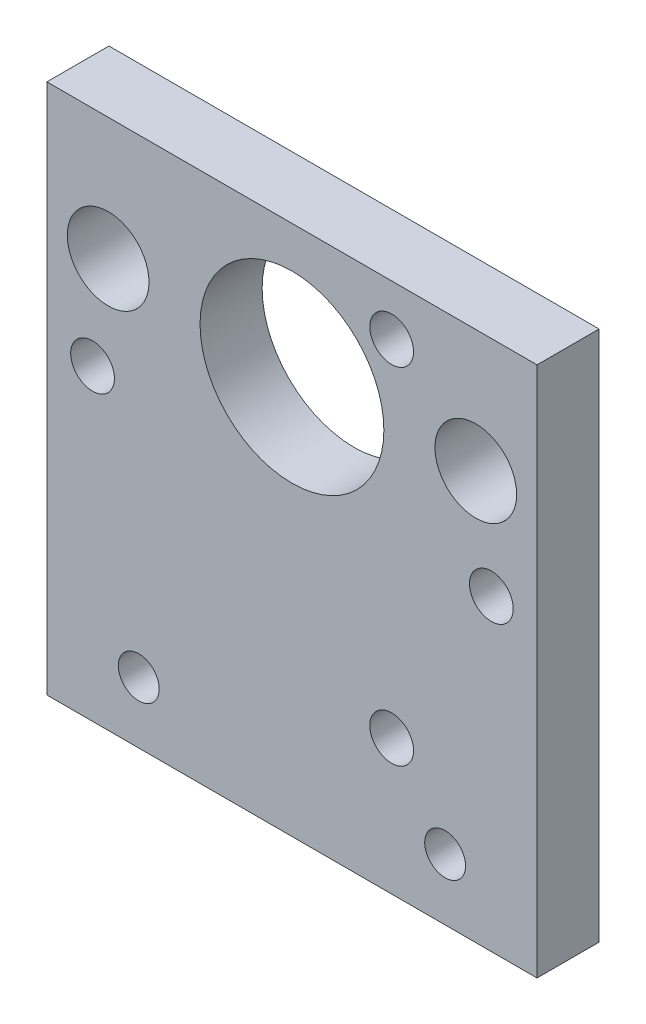
SolidWorks part; units mm, degrees
material "6063-O"
ref_plane "Front" through (0, 0, 0) normal (0, 0, 1) x (1, 0, 0)
ref_plane "Top" through (0, 0, 0) normal (0, 1, 0) x (1, 0, 0)
ref_plane "Right" through (0, 0, 0) normal (1, 0, 0) x (0, 0, -1)
sketch "Sketch1" plane through (0, 0, 0) normal (0, 0, 1) x (1, 0, 0)
  line L1 (19.05, -20.6375) -> (-19.05, -20.6375)
  line L2 (19.05, -20.6375) -> (19.05, 20.6375)
  line L3 (19.05, 20.6375) -> (-19.05, 20.6375)
  line L4 (-19.05, -20.6375) -> (-19.05, 20.6375)
  line L5 (19.05, -20.6375) -> (-19.05, 20.6375) construction
  line L6 (19.05, 20.6375) -> (-19.05, -20.6375) construction
  point P0 (0, 0)
  dimension "D1" = 38.1
  dimension "D2" = 41.275
extrude "Boss-Extrude1" add sketch "Sketch1" along normal blind 4.826
sketch "Sketch2" plane through (0, 0, 4.826) normal (0, 0, 1) x (1, 0, 0)
  line L0 (19.05, 20.6375) -> (-19.05, 20.6375) construction
  line L1 (0, 0) -> (0, 18.787) construction
  line L2 (-15.5, 3.287) -> (15.5, 3.287) construction
  line L3 (7.75, -10.1364) -> (0, 3.287) construction
  line L4 (0, 3.287) -> (7.75, 16.7104) construction
  line L5 (-14.2875, 11.1125) -> (14.2875, 11.1125) construction
  line L6 (-19.05, 20.6375) -> (-19.05, -20.6375) construction
  circle A0 centre (0, 10.287) radius 7.1438
  circle A1 centre (0, 3.287) radius 15.5 construction
  circle A4 centre (7.75, 16.7104) radius 1.7
  circle A5 centre (7.75, -10.1364) radius 1.7
  circle A6 centre (-15.5, 3.287) radius 1.7
  circle A7 centre (15.5, 3.287) radius 1.7
  circle A8 centre (-14.2875, 11.1125) radius 3.175
  circle A9 centre (14.2875, 11.1125) radius 3.175
  point P23 (0, 11.1125)
  dimension "D2" = 14.2875
  dimension "D3" = 31
  dimension "D5" = 3.4
  dimension "D10" = 6.35
  dimension "D1" = 10.3505
  dimension "D4" = 7
  dimension "D6" = 120
  dimension "D7" = 30
  dimension "D8" = 9.525
  dimension "D9" = 4.7625
extrude "Cut-Extrude1" cut sketch "Sketch2" against normal through all contours A0
hole_wizard "Ø3.4 (3.4) Diameter Hole1" positions "Sketch3" profile "Sketch4" hole size "Ø3.4" standard "ANSI Metric" end condition through all
sketch "Sketch3" plane through (0, 0, 4.826) normal (0, 0, 1) x (1, 0, 0)
  point P0 (-15.5, 3.287)
  point P3 (7.75, 16.7104)
  point P6 (15.5, 3.287)
  point P9 (7.75, -10.1364)
sketch "Sketch4" plane through (-15.5, 3.287, 4.826) normal (1, 0, 0) x (0, -1, 0)
  line L0 (0, 0) -> (0, 4.826)
  line L1 (0, 4.826) -> (1.7, 4.826)
  line L2 (1.7, 4.826) -> (1.7, 0)
  line L5 (1.7, 0) -> (0, 0)
  line L11 (0, -6.35) -> (0, 107.95) construction
  dimension "Thru Hole Dia." = 3.4
  dimension "Thru Hole Depth" = 4.826
hole_wizard "1/4 (0.25) Diameter Hole1" positions "Sketch5" profile "Sketch6" hole size "1/4" standard "ANSI Inch" end condition through all
sketch "Sketch5" plane through (0, 0, 4.826) normal (0, 0, 1) x (1, 0, 0)
  point P0 (-14.2875, 11.1125)
  point P3 (14.2875, 11.1125)
sketch "Sketch6" plane through (-14.2875, 11.1125, 4.826) normal (1, 0, 0) x (0, -1, 0)
  line L0 (0, 0) -> (0, 4.826)
  line L1 (0, 4.826) -> (3.175, 4.826)
  line L2 (3.175, 4.826) -> (3.175, 0)
  line L5 (3.175, 0) -> (0, 0)
  line L11 (0, -6.35) -> (0, 107.95) construction
  dimension "Thru Hole Dia." = 6.35
  dimension "Thru Hole Depth" = 4.826
sketch "Sketch7" plane through (0, 0, 4.826) normal (0, 0, 1) x (1, 0, 0)
  line L0 (-11.9062, -15.875) -> (11.9063, -15.875) construction
  line L3 (-19.05, -20.6375) -> (19.05, -20.6375) construction
  line L4 (0, 0) -> (0, -15.875) construction
  circle A0 centre (-11.9062, -15.875) radius 1.5875
  circle A1 centre (11.9063, -15.875) radius 1.5875
  dimension "D1" = 3.175
  dimension "D2" = 4.7625
  dimension "D3" = 23.8125
hole_wizard "1/8 (0.125) Clearance Dowel Hole1" positions "Sketch10" profile "Sketch11" hole size "1/8" standard "ANSI Inch" end condition through all
sketch "Sketch10" plane through (0, 0, 4.826) normal (0, 0, 1) x (1, 0, 0)
  point P0 (-11.9062, -15.875)
  point P3 (11.9063, -15.875)
sketch "Sketch11" plane through (-11.9062, -15.875, 4.826) normal (1, 0, 0) x (0, -1, 0)
  line L0 (0, 0) -> (0, 4.826)
  line L1 (0, 4.826) -> (1.5875, 4.826)
  line L2 (1.5875, 4.826) -> (1.5875, 0)
  line L5 (1.5875, 0) -> (0, 0)
  line L11 (0, -6.35) -> (0, 107.95) construction
  dimension "Thru Hole Dia." = 3.175
  dimension "Thru Hole Depth" = 4.826
